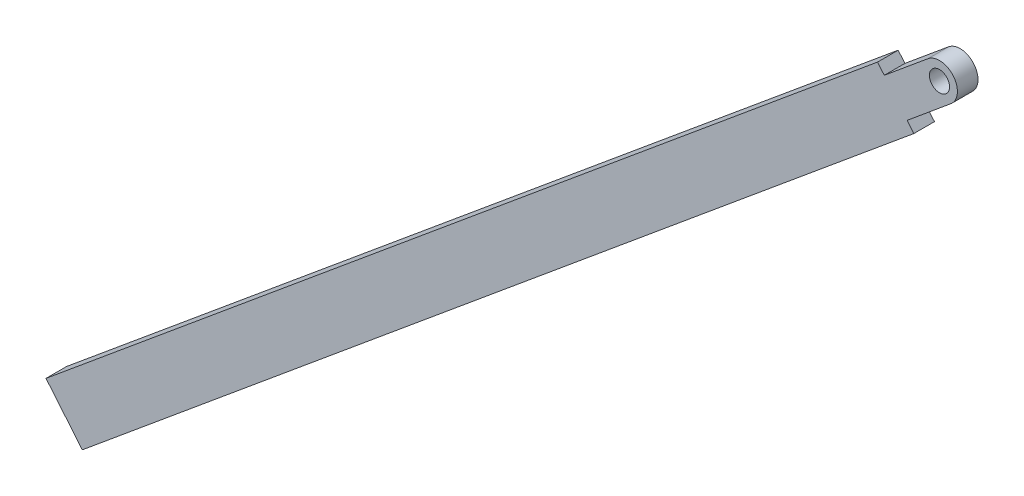
SolidWorks part; units mm, degrees
ref_plane "Alzado" through (0, 0, 0) normal (0, 0, 1) x (1, 0, 0)
ref_plane "Planta" through (0, 0, 0) normal (0, 1, 0) x (1, 0, 0)
ref_plane "Vista lateral" through (0, 0, 0) normal (1, 0, 0) x (0, 0, -1)
sketch "Sketch1" plane through (0, 0, 0) normal (0, 0, 1) x (1, 0, 0)
  line L0 (4, 299.8) -> (-242.0913, 95.6913) construction
  line L1 (6.5536, 296.7212) -> (-3.2217, 288.6135)
  line L2 (1.4464, 302.8788) -> (-8.3289, 294.7712)
  line L3 (-9.8291, 296.58) -> (-195.5286, 142.5604)
  line L4 (-1.7215, 286.8047) -> (-187.421, 132.7851)
  line L5 (-110.6776, 212.936) -> (-102.57, 203.1607) construction
  line L6 (-9.8291, 296.58) -> (-8.3289, 294.7712)
  line L7 (-3.2217, 288.6135) -> (-1.7215, 286.8047)
  line L8 (-187.421, 132.7851) -> (-197.7135, 114.2435) construction
  line L9 (-110, 65) -> (-254.6299, 135.2206) construction
  line L10 (-187.421, 132.7851) -> (-195.5286, 142.5604)
  arc A0 (6.5536, 296.7212) -> (1.4464, 302.8788) centre (4, 299.8) ccw
  circle A2 centre (-110, 65) radius 101.6 construction
  circle A3 centre (-110, 65) radius 101.6 construction
  circle A4 centre (-110, 65) radius 107.95 construction
  circle A5 centre (4, 299.8) radius 261.0116 construction
  circle A6 centre (-108.8822, 64.9326) radius 101.6 construction
  point P1 (-191.0127, 126.3148)
  point P19 (-106.6238, 208.0484)
  dimension "D1" = 8
  dimension "D3" = 12.7
  dimension "D4" = 12.7
  dimension "D2" = 6.35
extrude "Boss-Extrude1" add sketch "Sketch1" along normal blind 4.6
sketch "Sketch2" plane through (0, 0, 4.6) normal (0, 0, 1) x (1, 0, 0)
  circle A0 centre (4, 299.8) radius 2.25
extrude "Cut-Extrude1" cut sketch "Sketch2" against normal through all
